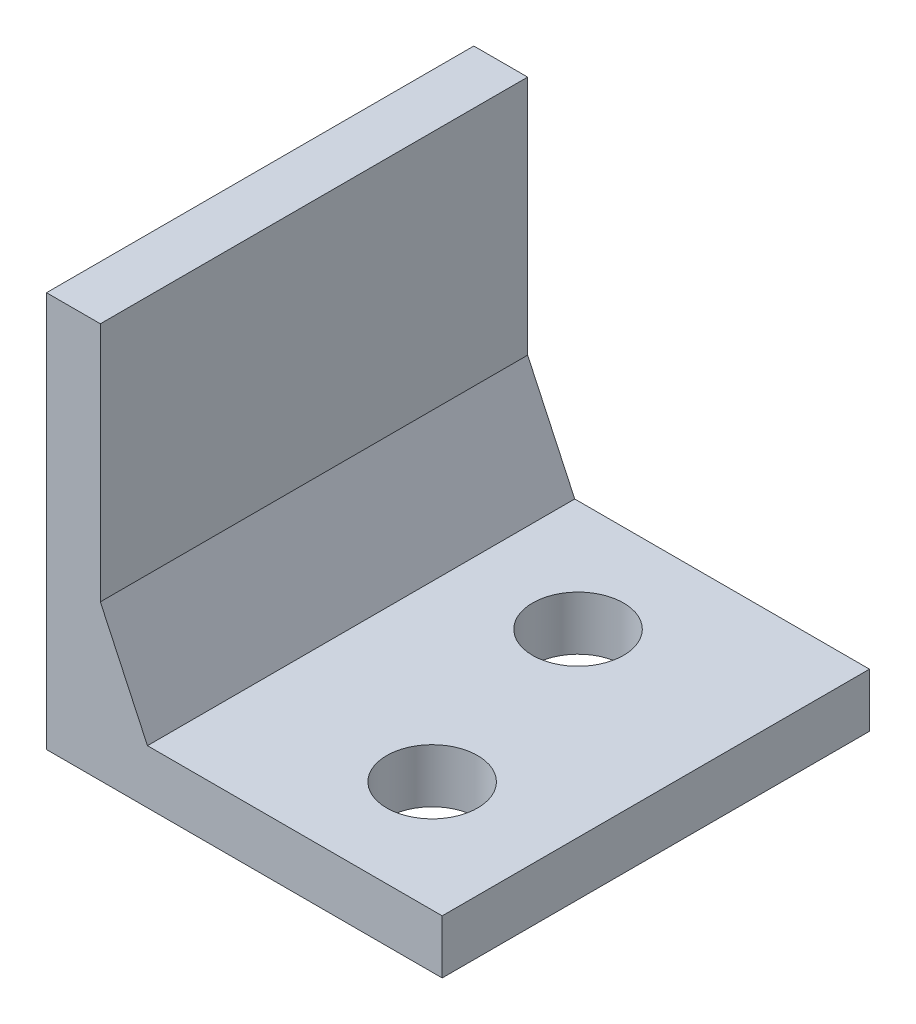
SolidWorks part; units mm, degrees
material "ABS"
ref_plane "Front Plane" through (0, 0, 0) normal (0, 0, 1) x (1, 0, 0)
ref_plane "Top Plane" through (0, 0, 0) normal (0, 1, 0) x (1, 0, 0)
ref_plane "Right Plane" through (0, 0, 0) normal (1, 0, 0) x (0, 0, -1)
sketch "Sketch1" plane through (0, 0, 0) normal (0, 0, 1) x (1, 0, 0)
  line L0 (0, 0) -> (0, 29.4)
  line L1 (0, 29.4) -> (4, 29.4)
  line L2 (4, 29.4) -> (4, 4)
  line L3 (4, 4) -> (29.4, 4)
  line L4 (29.4, 4) -> (29.4, 0)
  line L5 (29.4, 0) -> (0, 0)
  dimension "D1" = 4
  dimension "D2" = 25.4
  dimension "D3" = 25.4
extrude "Boss-Extrude1" add sketch "Sketch1" along normal blind 31.75
hole_wizard "1/4 Clearance Hole1" positions "Sketch2" profile "Sketch3" hole size "1/4" standard "ANSI Inch" end condition through all
sketch "Sketch2" plane through (0, 4, 0) normal (0, 1, 0) x (1, 0, 0)
  line L0 (4, -31.75) -> (4, 0) construction
  line L1 (29.4, -31.75) -> (29.4, 0) construction
  point P0 (20.4, -23.495)
  point P2 (16, -8.255)
  point P10 (29.4, -15.875)
  dimension "D1" = 16.4
  dimension "D2" = 12
  dimension "D3" = 15.24
  dimension "D4" = 7.62
sketch "Sketch3" plane through (20.4, 4, 23.495) normal (1, 0, 0) x (0, 0, 1)
  line L0 (0, 0) -> (0, 4)
  line L1 (0, 4) -> (3.3782, 4)
  line L2 (3.3782, 4) -> (3.3782, 0)
  line L5 (3.3782, 0) -> (0, 0)
  line L11 (0, -6.35) -> (0, 107.95) construction
  dimension "Thru Hole Dia." = 6.7564
  dimension "Thru Hole Depth" = 4
chamfer "Chamfer1" distance 3.5 angle 65 1 edges at (4, 4, 15.875)
equation "\"D4@Sketch2\"=\"D3@Sketch2\"/2"
